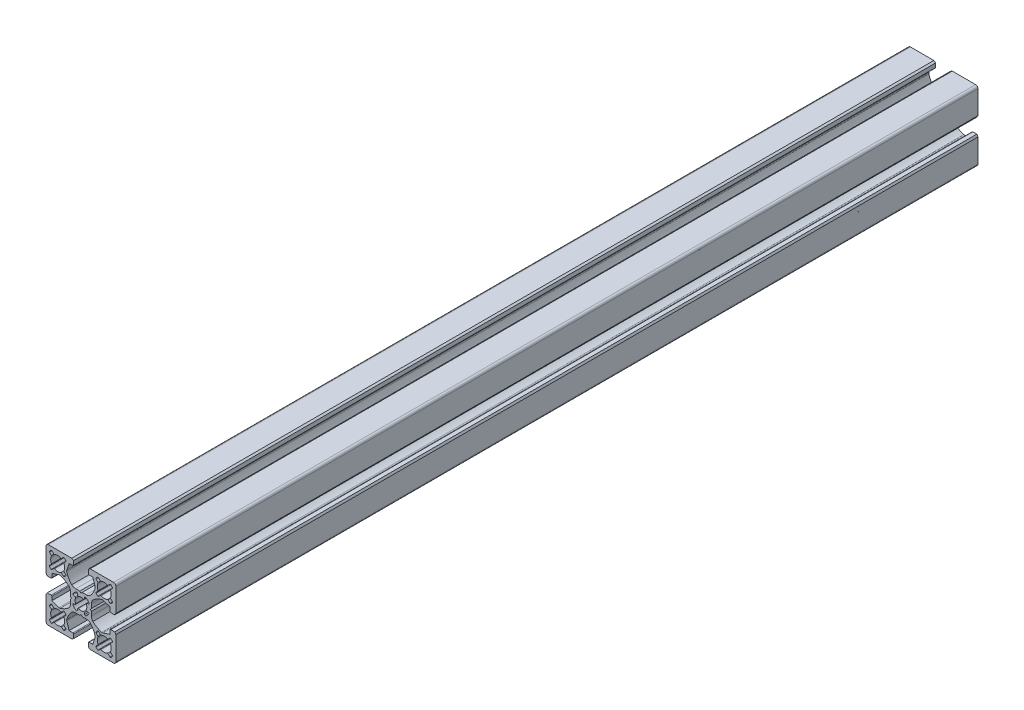
SolidWorks part; units mm, degrees
ref_plane "정면" through (0, 0, 0) normal (0, 0, 1) x (1, 0, 0)
ref_plane "윗면" through (0, 0, 0) normal (0, 1, 0) x (1, 0, 0)
ref_plane "우측면" through (0, 0, 0) normal (1, 0, 0) x (0, 0, -1)
sketch "Model" plane through (0, 0, 0) normal (0, 0, 1) x (1, 0, 0)
  line L0 (465.6218, 205.5838) -> (465.6218, 209.9838) construction
  line L1 (463.4218, 207.7838) -> (467.8218, 207.7838) construction
  line L2 (462.8793, 206.102) -> (462.1388, 205.3614)
  line L3 (463.1994, 204.3007) -> (463.94, 205.0413)
  line L4 (467.3037, 205.0413) -> (468.0443, 204.3007)
  line L5 (469.1049, 205.3614) -> (468.3643, 206.102)
  line L6 (468.3643, 209.4657) -> (469.1049, 210.2063)
  line L7 (468.0443, 211.2669) -> (467.3037, 210.5263)
  line L8 (463.94, 210.5263) -> (463.1994, 211.2669)
  line L9 (462.1388, 210.2063) -> (462.8793, 209.4657)
  line L10 (463.4211, 187.7832) -> (467.8211, 187.7829) construction
  line L11 (465.6212, 189.9831) -> (465.6209, 185.5831) construction
  line L12 (462.8787, 189.4651) -> (462.1382, 190.2057)
  line L13 (463.1989, 191.2663) -> (463.9394, 190.5257)
  line L14 (467.3031, 190.5254) -> (468.0438, 191.2659)
  line L15 (469.1043, 190.2052) -> (468.3637, 189.4647)
  line L16 (468.3634, 186.101) -> (469.1039, 185.3604)
  line L17 (468.0432, 184.2998) -> (467.3027, 185.0404)
  line L18 (463.939, 185.0407) -> (463.1984, 184.3002)
  line L19 (462.1378, 185.3609) -> (462.8784, 186.1014)
  line L20 (448.3673, 189.4651) -> (449.1078, 190.2057)
  line L21 (448.0471, 191.2663) -> (447.3066, 190.5257)
  line L22 (443.9429, 190.5254) -> (443.2023, 191.2659)
  line L23 (442.1417, 190.2052) -> (442.8823, 189.4647)
  line L24 (442.8826, 186.101) -> (442.1421, 185.3604)
  line L25 (443.2028, 184.2998) -> (443.9433, 185.0404)
  line L26 (447.307, 185.0407) -> (448.0476, 184.3002)
  line L27 (449.1082, 185.3609) -> (448.3676, 186.1014)
  line L28 (445.6248, 189.9831) -> (445.6251, 185.5831) construction
  line L29 (447.825, 187.7832) -> (443.425, 187.7829) construction
  line L30 (447.8242, 207.7838) -> (443.4242, 207.7838) construction
  line L31 (445.6242, 205.5838) -> (445.6242, 209.9838) construction
  line L32 (471.0819, 197.7838) -> (439.4, 197.7838) construction
  line L33 (455.6242, 181.8427) -> (455.6242, 213.7801) construction
  line L34 (457.2103, 201.0212) -> (457.0767, 200.2802)
  line L35 (454.1716, 200.2802) -> (454.0381, 201.0212)
  line L36 (452.3868, 199.37) -> (453.1278, 199.2364)
  line L37 (453.1278, 196.3313) -> (452.3868, 196.1977)
  line L38 (454.0381, 194.5465) -> (454.1716, 195.2874)
  line L39 (457.0767, 195.2874) -> (457.2103, 194.5465)
  line L40 (458.8615, 196.1977) -> (458.1206, 196.3313)
  line L41 (458.1206, 199.2364) -> (458.8615, 199.37)
  line L42 (448.3667, 206.102) -> (449.1073, 205.3614)
  line L43 (448.0466, 204.3007) -> (447.306, 205.0413)
  line L44 (443.9423, 205.0413) -> (443.2018, 204.3007)
  line L45 (442.1411, 205.3614) -> (442.8817, 206.102)
  line L46 (442.8817, 209.4657) -> (442.1411, 210.2063)
  line L47 (443.2018, 211.2669) -> (443.9423, 210.5263)
  line L48 (447.306, 210.5263) -> (448.0466, 211.2669)
  line L49 (449.1073, 210.2063) -> (448.3667, 209.4657)
  line L50 (459.5742, 182.7838) -> (458.7742, 183.2838)
  line L51 (458.7742, 183.2838) -> (458.7742, 184.9838)
  line L52 (459.0742, 185.2838) -> (460.7242, 185.2838)
  line L53 (460.7242, 185.2838) -> (461.7118, 188.3356)
  line L54 (457.842, 193.2838) -> (456.1242, 193.2838)
  line L55 (456.1242, 193.2838) -> (455.6242, 193.7838)
  line L56 (455.6242, 193.7838) -> (455.1242, 193.2838)
  line L57 (455.1242, 193.2838) -> (453.4063, 193.2838)
  line L58 (449.5366, 188.3356) -> (450.5242, 185.2838)
  line L59 (450.5242, 185.2838) -> (452.1742, 185.2838)
  line L60 (452.4742, 184.9838) -> (452.4742, 183.2838)
  line L61 (452.4742, 183.2838) -> (451.6742, 182.7838)
  line L62 (451.6742, 182.7838) -> (441.6242, 182.7838)
  line L63 (440.6242, 183.7838) -> (440.6242, 193.8338)
  line L64 (440.6242, 193.8338) -> (441.1242, 194.6338)
  line L65 (441.1242, 194.6338) -> (442.8242, 194.6338)
  line L66 (443.1242, 194.3338) -> (443.1242, 192.6838)
  line L67 (443.1242, 192.6838) -> (446.1759, 191.6962)
  line L68 (451.1242, 195.566) -> (451.1242, 197.2838)
  line L69 (451.1242, 197.2838) -> (451.6242, 197.7838)
  line L70 (451.6242, 197.7838) -> (451.1242, 198.2838)
  line L71 (451.1242, 198.2838) -> (451.1242, 200.0017)
  line L72 (446.1759, 203.8714) -> (443.1242, 202.8838)
  line L73 (443.1242, 202.8838) -> (443.1242, 201.2338)
  line L74 (442.8242, 200.9338) -> (441.1242, 200.9338)
  line L75 (441.1242, 200.9338) -> (440.6242, 201.7338)
  line L76 (440.6242, 201.7338) -> (440.6242, 211.7838)
  line L77 (441.6242, 212.7838) -> (451.6742, 212.7838)
  line L78 (451.6742, 212.7838) -> (452.4742, 212.2838)
  line L79 (452.4742, 212.2838) -> (452.4742, 210.5838)
  line L80 (452.1742, 210.2838) -> (450.5242, 210.2838)
  line L81 (450.5242, 210.2838) -> (449.5366, 207.2321)
  line L82 (453.4063, 202.2838) -> (455.1242, 202.2838)
  line L83 (455.1242, 202.2838) -> (455.6242, 201.7838)
  line L84 (455.6242, 201.7838) -> (456.1242, 202.2838)
  line L85 (456.1242, 202.2838) -> (457.842, 202.2838)
  line L86 (461.7118, 207.2321) -> (460.7242, 210.2838)
  line L87 (460.7242, 210.2838) -> (459.0742, 210.2838)
  line L88 (458.7742, 210.5838) -> (458.7742, 212.2838)
  line L89 (458.7742, 212.2838) -> (459.5742, 212.7838)
  line L90 (459.5742, 212.7838) -> (469.6242, 212.7838)
  line L91 (470.6242, 211.7838) -> (470.6242, 201.7338)
  line L92 (470.6242, 201.7338) -> (470.1242, 200.9338)
  line L93 (470.1242, 200.9338) -> (468.4242, 200.9338)
  line L94 (468.1242, 201.2338) -> (468.1242, 202.8838)
  line L95 (468.1242, 202.8838) -> (465.0724, 203.8714)
  line L96 (460.1242, 200.0017) -> (460.1242, 198.2838)
  line L97 (460.1242, 198.2838) -> (459.6242, 197.7838)
  line L98 (459.6242, 197.7838) -> (460.1242, 197.2838)
  line L99 (460.1242, 197.2838) -> (460.1242, 195.566)
  line L100 (465.0724, 191.6962) -> (468.1242, 192.6838)
  line L101 (468.1242, 192.6838) -> (468.1242, 194.3338)
  line L102 (468.4242, 194.6338) -> (470.1242, 194.6338)
  line L103 (470.1242, 194.6338) -> (470.6242, 193.8338)
  line L104 (470.6242, 193.8338) -> (470.6242, 183.7838)
  line L105 (469.6242, 182.7838) -> (459.5742, 182.7838)
  arc A0 (462.8793, 206.102) -> (462.9358, 206.4477) centre (462.6672, 206.3141) ccw
  arc A1 (462.1388, 205.3614) -> (462.1172, 204.9611) centre (462.3509, 205.1493) ccw
  arc A2 (462.1172, 204.9611) -> (462.7991, 204.2792) centre (465.6218, 207.7838) ccw
  arc A3 (462.7991, 204.2792) -> (463.1994, 204.3007) centre (462.9873, 204.5129) ccw
  arc A4 (464.2857, 205.0978) -> (463.94, 205.0413) centre (464.1521, 204.8292) ccw
  arc A5 (464.2857, 205.0978) -> (466.9579, 205.0978) centre (465.6218, 207.7838) ccw
  arc A6 (467.3037, 205.0413) -> (466.9579, 205.0978) centre (467.0916, 204.8292) ccw
  arc A7 (468.0443, 204.3007) -> (468.4446, 204.2792) centre (468.2564, 204.5129) ccw
  arc A8 (468.4446, 204.2792) -> (469.1264, 204.9611) centre (465.6218, 207.7838) ccw
  arc A9 (469.1264, 204.9611) -> (469.1049, 205.3614) centre (468.8928, 205.1493) ccw
  arc A10 (468.3079, 206.4477) -> (468.3643, 206.102) centre (468.5765, 206.3141) ccw
  arc A11 (468.3079, 206.4477) -> (468.3079, 209.1199) centre (465.6218, 207.7838) ccw
  arc A12 (468.3643, 209.4657) -> (468.3079, 209.1199) centre (468.5765, 209.2536) ccw
  arc A13 (469.1049, 210.2063) -> (469.1264, 210.6066) centre (468.8928, 210.4184) ccw
  arc A14 (469.1264, 210.6066) -> (468.4446, 211.2884) centre (465.6218, 207.7838) ccw
  arc A15 (468.4446, 211.2884) -> (468.0443, 211.2669) centre (468.2564, 211.0548) ccw
  arc A16 (466.9579, 210.4699) -> (467.3037, 210.5263) centre (467.0916, 210.7385) ccw
  arc A17 (466.9579, 210.4699) -> (464.2857, 210.4699) centre (465.6218, 207.7838) ccw
  arc A18 (463.94, 210.5263) -> (464.2857, 210.4699) centre (464.1521, 210.7385) ccw
  arc A19 (463.1994, 211.2669) -> (462.7991, 211.2884) centre (462.9873, 211.0548) ccw
  arc A20 (462.7991, 211.2884) -> (462.1172, 210.6066) centre (465.6218, 207.7838) ccw
  arc A21 (462.1172, 210.6066) -> (462.1388, 210.2063) centre (462.3509, 210.4184) ccw
  arc A22 (462.9358, 209.1199) -> (462.8793, 209.4657) centre (462.6672, 209.2536) ccw
  arc A23 (462.9358, 209.1199) -> (462.9358, 206.4477) centre (465.6218, 207.7838) ccw
  arc A24 (462.9351, 189.1194) -> (462.8787, 189.4651) centre (462.6665, 189.253) ccw
  arc A25 (462.1167, 190.6061) -> (462.1382, 190.2057) centre (462.3503, 190.4179) ccw
  arc A26 (462.7986, 191.2879) -> (462.1167, 190.6061) centre (465.6211, 187.7831) ccw
  arc A27 (463.1989, 191.2663) -> (462.7986, 191.2879) centre (462.9868, 191.0542) ccw
  arc A28 (463.9394, 190.5257) -> (464.2852, 190.4692) centre (464.1516, 190.7378) ccw
  arc A29 (466.9574, 190.469) -> (464.2852, 190.4692) centre (465.6211, 187.7831) ccw
  arc A30 (466.9574, 190.469) -> (467.3031, 190.5254) centre (467.091, 190.7376) ccw
  arc A31 (468.4441, 191.2874) -> (468.0438, 191.2659) centre (468.2559, 191.0538) ccw
  arc A32 (469.1259, 190.6055) -> (468.4441, 191.2874) centre (465.6211, 187.7831) ccw
  arc A33 (469.1043, 190.2052) -> (469.1259, 190.6055) centre (468.8922, 190.4174) ccw
  arc A34 (468.3637, 189.4647) -> (468.3072, 189.119) centre (468.5758, 189.2525) ccw
  arc A35 (468.307, 186.4467) -> (468.3072, 189.119) centre (465.6211, 187.7831) ccw
  arc A36 (468.307, 186.4467) -> (468.3634, 186.101) centre (468.5756, 186.3131) ccw
  arc A37 (469.1254, 184.96) -> (469.1039, 185.3604) centre (468.8918, 185.1482) ccw
  arc A38 (468.4435, 184.2782) -> (469.1254, 184.96) centre (465.6211, 187.7831) ccw
  arc A39 (468.0432, 184.2998) -> (468.4435, 184.2782) centre (468.2554, 184.5119) ccw
  arc A40 (467.3027, 185.0404) -> (466.957, 185.0969) centre (467.0905, 184.8283) ccw
  arc A41 (464.2847, 185.0971) -> (466.957, 185.0969) centre (465.6211, 187.7831) ccw
  arc A42 (464.2847, 185.0971) -> (463.939, 185.0407) centre (464.1511, 184.8285) ccw
  arc A43 (462.798, 184.2787) -> (463.1984, 184.3002) centre (462.9862, 184.5123) ccw
  arc A44 (462.1162, 184.9606) -> (462.798, 184.2787) centre (465.6211, 187.7831) ccw
  arc A45 (462.1378, 185.3609) -> (462.1162, 184.9606) centre (462.3499, 185.1488) ccw
  arc A46 (462.8784, 186.1014) -> (462.9349, 186.4472) centre (462.6663, 186.3136) ccw
  arc A47 (462.9351, 189.1194) -> (462.9349, 186.4472) centre (465.6211, 187.7831) ccw
  arc A48 (448.3673, 189.4651) -> (448.3109, 189.1194) centre (448.5795, 189.253) ccw
  arc A49 (449.1078, 190.2057) -> (449.1293, 190.6061) centre (448.8957, 190.4179) ccw
  arc A50 (449.1293, 190.6061) -> (448.4474, 191.2879) centre (445.625, 187.7831) ccw
  arc A51 (448.4474, 191.2879) -> (448.0471, 191.2663) centre (448.2593, 191.0542) ccw
  arc A52 (446.9609, 190.4692) -> (447.3066, 190.5257) centre (447.0944, 190.7378) ccw
  arc A53 (446.9609, 190.4692) -> (444.2886, 190.469) centre (445.625, 187.7831) ccw
  arc A54 (443.9429, 190.5254) -> (444.2886, 190.469) centre (444.155, 190.7376) ccw
  arc A55 (443.2023, 191.2659) -> (442.8019, 191.2874) centre (442.9901, 191.0538) ccw
  arc A56 (442.8019, 191.2874) -> (442.1201, 190.6055) centre (445.625, 187.7831) ccw
  arc A57 (442.1201, 190.6055) -> (442.1417, 190.2052) centre (442.3538, 190.4174) ccw
  arc A58 (442.9388, 189.119) -> (442.8823, 189.4647) centre (442.6702, 189.2525) ccw
  arc A59 (442.9388, 189.119) -> (442.939, 186.4467) centre (445.625, 187.7831) ccw
  arc A60 (442.8826, 186.101) -> (442.939, 186.4467) centre (442.6704, 186.3131) ccw
  arc A61 (442.1421, 185.3604) -> (442.1206, 184.96) centre (442.3542, 185.1482) ccw
  arc A62 (442.1206, 184.96) -> (442.8025, 184.2782) centre (445.625, 187.7831) ccw
  arc A63 (442.8025, 184.2782) -> (443.2028, 184.2998) centre (442.9907, 184.5119) ccw
  arc A64 (444.2891, 185.0969) -> (443.9433, 185.0404) centre (444.1555, 184.8283) ccw
  arc A65 (444.2891, 185.0969) -> (446.9613, 185.0971) centre (445.625, 187.7831) ccw
  arc A66 (447.307, 185.0407) -> (446.9613, 185.0971) centre (447.0949, 184.8285) ccw
  arc A67 (448.0476, 184.3002) -> (448.448, 184.2787) centre (448.2598, 184.5123) ccw
  arc A68 (448.448, 184.2787) -> (449.1298, 184.9606) centre (445.625, 187.7831) ccw
  arc A69 (449.1298, 184.9606) -> (449.1082, 185.3609) centre (448.8961, 185.1488) ccw
  arc A70 (448.3111, 186.4472) -> (448.3676, 186.1014) centre (448.5797, 186.3136) ccw
  arc A71 (448.3111, 186.4472) -> (448.3109, 189.1194) centre (445.625, 187.7831) ccw
  arc A72 (458.8615, 199.37) -> (459.0666, 199.8178) centre (458.8083, 199.6652) ccw
  arc A73 (459.0666, 199.8178) -> (457.6582, 201.2262) centre (455.623, 197.7827) ccw
  arc A74 (457.6582, 201.2262) -> (457.2103, 201.0212) centre (457.5055, 200.9679) ccw
  arc A75 (456.6575, 200.0603) -> (457.0767, 200.2802) centre (456.7815, 200.3335) ccw
  arc A76 (456.6575, 200.0603) -> (454.5909, 200.0603) centre (455.6242, 197.7838) ccw
  arc A77 (454.1716, 200.2802) -> (454.5909, 200.0603) centre (454.4669, 200.3335) ccw
  arc A78 (454.0381, 201.0212) -> (453.5902, 201.2262) centre (453.7428, 200.9679) ccw
  arc A79 (453.5902, 201.2262) -> (452.1818, 199.8178) centre (455.6253, 197.7827) ccw
  arc A80 (452.1818, 199.8178) -> (452.3868, 199.37) centre (452.4401, 199.6652) ccw
  arc A81 (453.3477, 198.8171) -> (453.1278, 199.2364) centre (453.0745, 198.9411) ccw
  arc A82 (453.3477, 198.8171) -> (453.3477, 196.7505) centre (455.6242, 197.7838) ccw
  arc A83 (453.1278, 196.3313) -> (453.3477, 196.7505) centre (453.0745, 196.6265) ccw
  arc A84 (452.3868, 196.1977) -> (452.1818, 195.7498) centre (452.4401, 195.9025) ccw
  arc A85 (452.1818, 195.7498) -> (453.5902, 194.3414) centre (455.6253, 197.785) ccw
  arc A86 (453.5902, 194.3414) -> (454.0381, 194.5465) centre (453.7428, 194.5997) ccw
  arc A87 (454.5909, 195.5074) -> (454.1716, 195.2874) centre (454.4669, 195.2342) ccw
  arc A88 (454.5909, 195.5074) -> (456.6575, 195.5074) centre (455.6242, 197.7838) ccw
  arc A89 (457.0767, 195.2874) -> (456.6575, 195.5074) centre (456.7815, 195.2342) ccw
  arc A90 (457.2103, 194.5465) -> (457.6582, 194.3414) centre (457.5055, 194.5997) ccw
  arc A91 (457.6582, 194.3414) -> (459.0666, 195.7498) centre (455.623, 197.785) ccw
  arc A92 (459.0666, 195.7498) -> (458.8615, 196.1977) centre (458.8083, 195.9025) ccw
  arc A93 (457.9006, 196.7505) -> (458.1206, 196.3313) centre (458.1738, 196.6265) ccw
  arc A94 (457.9006, 196.7505) -> (457.9006, 198.8171) centre (455.6242, 197.7838) ccw
  arc A95 (458.1206, 199.2364) -> (457.9006, 198.8171) centre (458.1738, 198.9411) ccw
  arc A96 (448.3102, 206.4477) -> (448.3667, 206.102) centre (448.5788, 206.3141) ccw
  arc A97 (449.1288, 204.9611) -> (449.1073, 205.3614) centre (448.8951, 205.1493) ccw
  arc A98 (448.4469, 204.2792) -> (449.1288, 204.9611) centre (445.6242, 207.7838) ccw
  arc A99 (448.0466, 204.3007) -> (448.4469, 204.2792) centre (448.2587, 204.5129) ccw
  arc A100 (447.306, 205.0413) -> (446.9603, 205.0978) centre (447.0939, 204.8292) ccw
  arc A101 (444.2881, 205.0978) -> (446.9603, 205.0978) centre (445.6242, 207.7838) ccw
  arc A102 (444.2881, 205.0978) -> (443.9423, 205.0413) centre (444.1545, 204.8292) ccw
  arc A103 (442.8014, 204.2792) -> (443.2018, 204.3007) centre (442.9896, 204.5129) ccw
  arc A104 (442.1196, 204.9611) -> (442.8014, 204.2792) centre (445.6242, 207.7838) ccw
  arc A105 (442.1411, 205.3614) -> (442.1196, 204.9611) centre (442.3532, 205.1493) ccw
  arc A106 (442.8817, 206.102) -> (442.9381, 206.4477) centre (442.6695, 206.3141) ccw
  arc A107 (442.9381, 209.1199) -> (442.9381, 206.4477) centre (445.6242, 207.7838) ccw
  arc A108 (442.9381, 209.1199) -> (442.8817, 209.4657) centre (442.6695, 209.2536) ccw
  arc A109 (442.1196, 210.6066) -> (442.1411, 210.2063) centre (442.3532, 210.4184) ccw
  arc A110 (442.8014, 211.2884) -> (442.1196, 210.6066) centre (445.6242, 207.7838) ccw
  arc A111 (443.2018, 211.2669) -> (442.8014, 211.2884) centre (442.9896, 211.0548) ccw
  arc A112 (443.9423, 210.5263) -> (444.2881, 210.4699) centre (444.1545, 210.7385) ccw
  arc A113 (446.9603, 210.4699) -> (444.2881, 210.4699) centre (445.6242, 207.7838) ccw
  arc A114 (446.9603, 210.4699) -> (447.306, 210.5263) centre (447.0939, 210.7385) ccw
  arc A115 (448.4469, 211.2884) -> (448.0466, 211.2669) centre (448.2587, 211.0548) ccw
  arc A116 (449.1288, 210.6066) -> (448.4469, 211.2884) centre (445.6242, 207.7838) ccw
  arc A117 (449.1073, 210.2063) -> (449.1288, 210.6066) centre (448.8951, 210.4184) ccw
  arc A118 (448.3667, 209.4657) -> (448.3102, 209.1199) centre (448.5788, 209.2536) ccw
  arc A119 (448.3102, 206.4477) -> (448.3102, 209.1199) centre (445.6242, 207.7838) ccw
  arc A120 (459.0742, 185.2838) -> (458.7742, 184.9838) centre (459.0742, 184.9838) ccw
  arc A121 (461.7118, 188.3356) -> (461.7375, 188.856) centre (460.7604, 188.6435) ccw
  arc A122 (461.7375, 188.856) -> (459.6282, 192.6941) centre (452.2648, 186.1487) ccw
  arc A123 (459.6282, 192.6941) -> (457.842, 193.2838) centre (457.842, 190.2838) ccw
  arc A124 (453.4063, 193.2838) -> (451.6202, 192.6941) centre (453.4063, 190.2838) ccw
  arc A125 (451.6202, 192.6941) -> (449.5108, 188.856) centre (458.9836, 186.1487) ccw
  arc A126 (449.5108, 188.856) -> (449.5366, 188.3356) centre (450.488, 188.6435) ccw
  arc A127 (452.4742, 184.9838) -> (452.1742, 185.2838) centre (452.1742, 184.9838) ccw
  arc A128 (440.6242, 183.7838) -> (441.6242, 182.7838) centre (441.6242, 183.7838) ccw
  arc A129 (443.1242, 194.3338) -> (442.8242, 194.6338) centre (442.8242, 194.3338) ccw
  arc A130 (446.1759, 191.6962) -> (446.6963, 191.6705) centre (446.4838, 192.6476) ccw
  arc A131 (446.6963, 191.6705) -> (450.5345, 193.7798) centre (443.9891, 201.1432) ccw
  arc A132 (450.5345, 193.7798) -> (451.1242, 195.566) centre (448.1242, 195.566) ccw
  arc A133 (451.1242, 200.0017) -> (450.5345, 201.7878) centre (448.1242, 200.0017) ccw
  arc A134 (450.5345, 201.7878) -> (446.6963, 203.8972) centre (443.9891, 194.4244) ccw
  arc A135 (446.6963, 203.8972) -> (446.1759, 203.8714) centre (446.4838, 202.92) ccw
  arc A136 (442.8242, 200.9338) -> (443.1242, 201.2338) centre (442.8242, 201.2338) ccw
  arc A137 (441.6242, 212.7838) -> (440.6242, 211.7838) centre (441.6242, 211.7838) ccw
  arc A138 (452.1742, 210.2838) -> (452.4742, 210.5838) centre (452.1742, 210.5838) ccw
  arc A139 (449.5366, 207.2321) -> (449.5108, 206.7117) centre (450.488, 206.9242) ccw
  arc A140 (449.5108, 206.7117) -> (451.6202, 202.8735) centre (458.9836, 209.4189) ccw
  arc A141 (451.6202, 202.8735) -> (453.4063, 202.2838) centre (453.4063, 205.2838) ccw
  arc A142 (457.842, 202.2838) -> (459.6282, 202.8735) centre (457.842, 205.2838) ccw
  arc A143 (459.6282, 202.8735) -> (461.7375, 206.7117) centre (452.2648, 209.4189) ccw
  arc A144 (461.7375, 206.7117) -> (461.7118, 207.2321) centre (460.7604, 206.9242) ccw
  arc A145 (458.7742, 210.5838) -> (459.0742, 210.2838) centre (459.0742, 210.5838) ccw
  arc A146 (470.6242, 211.7838) -> (469.6242, 212.7838) centre (469.6242, 211.7838) ccw
  arc A147 (468.1242, 201.2338) -> (468.4242, 200.9338) centre (468.4242, 201.2338) ccw
  arc A148 (465.0724, 203.8714) -> (464.552, 203.8972) centre (464.7645, 202.92) ccw
  arc A149 (464.552, 203.8972) -> (460.7139, 201.7878) centre (467.2593, 194.4244) ccw
  arc A150 (460.7139, 201.7878) -> (460.1242, 200.0017) centre (463.1242, 200.0017) ccw
  arc A151 (460.1242, 195.566) -> (460.7139, 193.7798) centre (463.1242, 195.566) ccw
  arc A152 (460.7139, 193.7798) -> (464.552, 191.6705) centre (467.2593, 201.1432) ccw
  arc A153 (464.552, 191.6705) -> (465.0724, 191.6962) centre (464.7645, 192.6476) ccw
  arc A154 (468.4242, 194.6338) -> (468.1242, 194.3338) centre (468.4242, 194.3338) ccw
  arc A155 (469.6242, 182.7838) -> (470.6242, 183.7838) centre (469.6242, 183.7838) ccw
  dimension "D1" = 30
  dimension "D2" = 30
  dimension "D3" = 15
  dimension "D4" = 15
extrude "보스-돌출1" add sketch "Model" along normal blind 370
